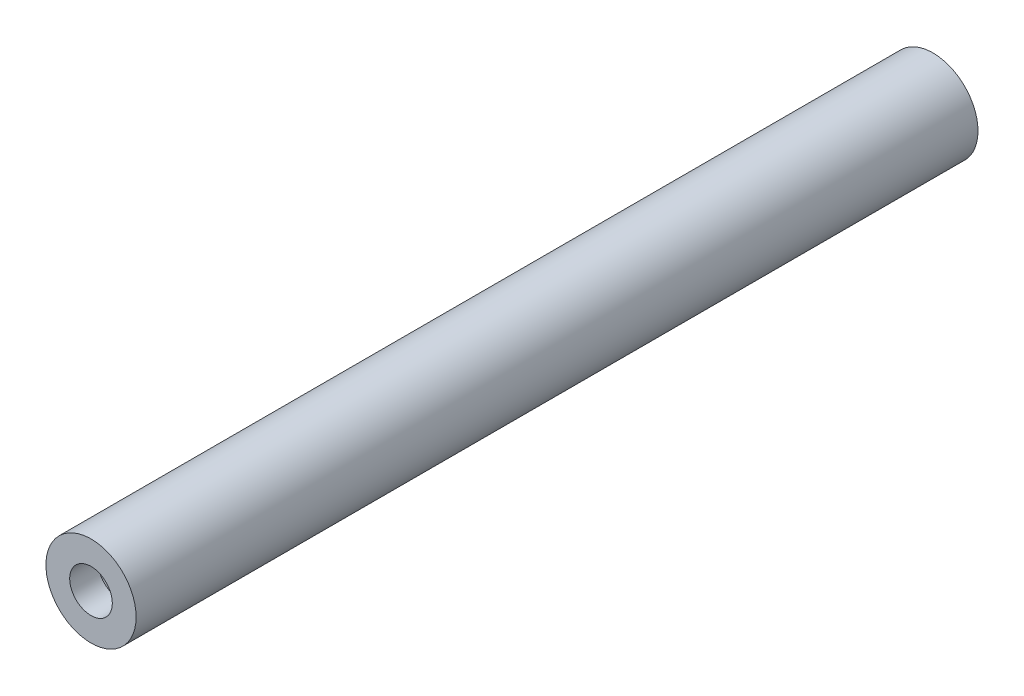
SolidWorks part; units mm, degrees
material "Acrylic (Medium-high impact)"
ref_plane "Front Plane" through (0, 0, 0) normal (0, 0, 1) x (1, 0, 0)
ref_plane "Top Plane" through (0, 0, 0) normal (0, 1, 0) x (1, 0, 0)
ref_plane "Right Plane" through (0, 0, 0) normal (1, 0, 0) x (0, 0, -1)
sketch "Sketch1" plane through (0, 0, 0) normal (0, 0, 1) x (1, 0, 0)
  circle A0 centre (0, 0) radius 4.7625
  dimension "D1" = 9.525
extrude "Boss-Extrude1" add sketch "Sketch1" against normal blind 88.9
sketch "Sketch2" plane through (0, 0, 0) normal (0, 0, 1) x (1, 0, 0)
  circle A0 centre (0, 0) radius 2.25
  dimension "D1" = 4.5
extrude "Cut-Extrude1" cut sketch "Sketch2" against normal blind 3
